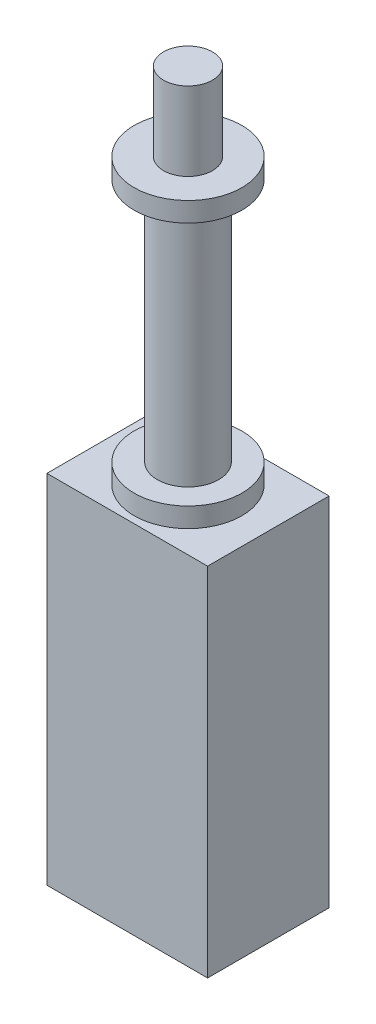
SolidWorks part; units mm, degrees
ref_plane "Front Plane" through (0, 0, 0) normal (0, 0, 1) x (1, 0, 0)
ref_plane "Top Plane" through (0, 0, 0) normal (0, 1, 0) x (1, 0, 0)
ref_plane "Right Plane" through (0, 0, 0) normal (1, 0, 0) x (0, 0, -1)
sketch "Sketch1" plane through (0, 0, 0) normal (0, 1, 0) x (1, 0, 0)
  circle A0 centre (0, 0) radius 34.925
  dimension "D1" = 69.85
extrude "Extrude1" add sketch "Sketch1" against normal blind 12.7
sketch "Sketch2" plane through (0, 0, 0) normal (0, 1, 0) x (1, 0, 0)
  circle A0 centre (0, 0) radius 19.866
extrude "Extrude2" add sketch "Sketch2" against normal blind 184.15
sketch "Sketch3" plane through (0, 0, 0) normal (0, 1, 0) x (1, 0, 0)
  circle A0 centre (0, 0) radius 15.875
  dimension "D1" = 31.75
extrude "Extrude3" add sketch "Sketch3" along normal blind 50.8
sketch "Sketch4" plane through (0, -184.15, 0) normal (0, -1, 0) x (1, 0, 0)
  circle A0 centre (0, 0) radius 34.925
extrude "Extrude4" add sketch "Sketch4" against normal blind 12.7
sketch "Sketch5" plane through (0, -184.15, 0) normal (0, -1, 0) x (1, 0, 0)
  line L0 (0, 0) -> (0, 20.4632) construction
  line L1 (0, 0) -> (14.244, 0) construction
  line L2 (-52.07, 39.37) -> (52.07, 39.37)
  line L3 (52.07, 39.37) -> (52.07, -39.37)
  line L4 (-52.07, 39.37) -> (-52.07, -39.37)
  line L5 (-52.07, -39.37) -> (52.07, -39.37)
  point P9 (0, 39.37)
  point P10 (52.07, 0)
  point P11 (-52.07, 0)
  dimension "D1" = 104.14
  dimension "D2" = 78.74
extrude "Extrude5" add sketch "Sketch5" along normal blind 231.14
